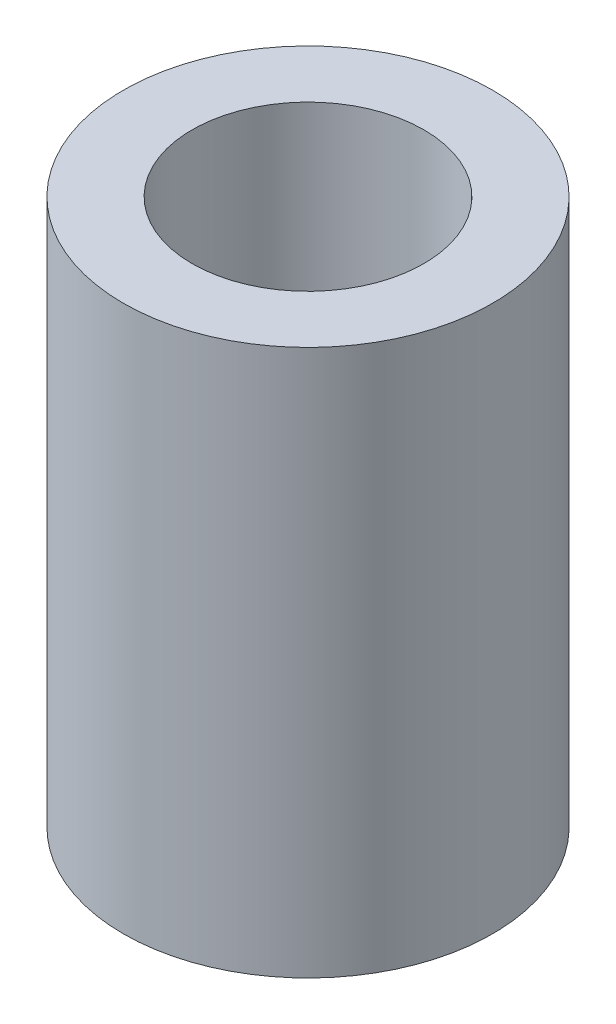
SolidWorks part; units mm, degrees
ref_plane "Front Plane" through (0, 0, 0) normal (0, 0, 1) x (1, 0, 0)
ref_plane "Top Plane" through (0, 0, 0) normal (0, 1, 0) x (1, 0, 0)
ref_plane "Right Plane" through (0, 0, 0) normal (1, 0, 0) x (0, 0, -1)
sketch "Sketch1" plane through (0, 0, 0) normal (0, 1, 0) x (1, 0, 0)
  circle A0 centre (0, 0) radius 3.375
  circle A1 centre (0, 0) radius 5.375
  dimension "D1" = 6.75
  dimension "D2" = 2
extrude "Boss-Extrude1" add sketch "Sketch1" along normal blind 15.9
